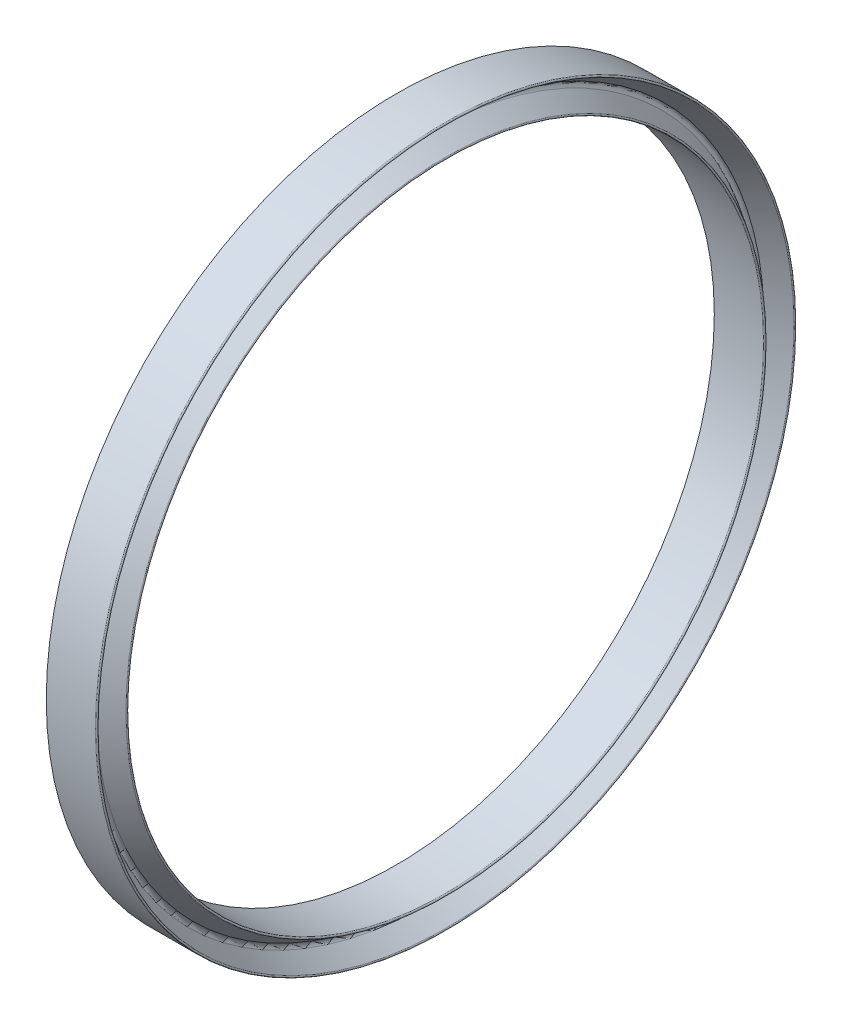
SolidWorks part; units mm, degrees
material "PP Copolymer"
ref_plane "Ön Düzlem" through (0, 0, 0) normal (0, 0, 1) x (1, 0, 0)
ref_plane "Üst Düzlem" through (0, 0, 0) normal (0, 1, 0) x (1, 0, 0)
ref_plane "Sağ Düzlem" through (0, 0, 0) normal (1, 0, 0) x (0, 0, -1)
sketch "Sketch1" plane through (0, 0, 0) normal (0, 0, 1) x (1, 0, 0)
  line L0 (-81.3053, 0) -> (83.2152, 0) construction
  line L1 (-65.1991, -33) -> (-60.5601, -33)
  line L2 (-65.1991, -30) -> (-60.5601, -30)
  line L3 (-65.1991, -33) -> (-65.1991, -30)
  line L4 (-60.5087, -30.1857) -> (-62.2704, -31.2428)
  line L5 (-62.2704, -31.7572) -> (-60.5087, -32.8143)
  arc A0 (-62.2704, -31.2428) -> (-62.2704, -31.7572) centre (-62.116, -31.5) ccw
  arc A1 (-60.5601, -30) -> (-60.5087, -30.1857) centre (-60.5601, -30.1) cw
  arc A2 (-60.5087, -32.8143) -> (-60.5601, -33) centre (-60.5601, -32.9) cw
  point P12 (-60.1991, -30)
  point P15 (-60.1991, -33)
  dimension "D5" = 0.3
  dimension "D6" = 0.1
  dimension "D1" = 33
  dimension "D2" = 30
  dimension "D3" = 5
  dimension "D4" = 5
revolve "Revolve1" add sketch "Sketch1" angle 360 about L0
